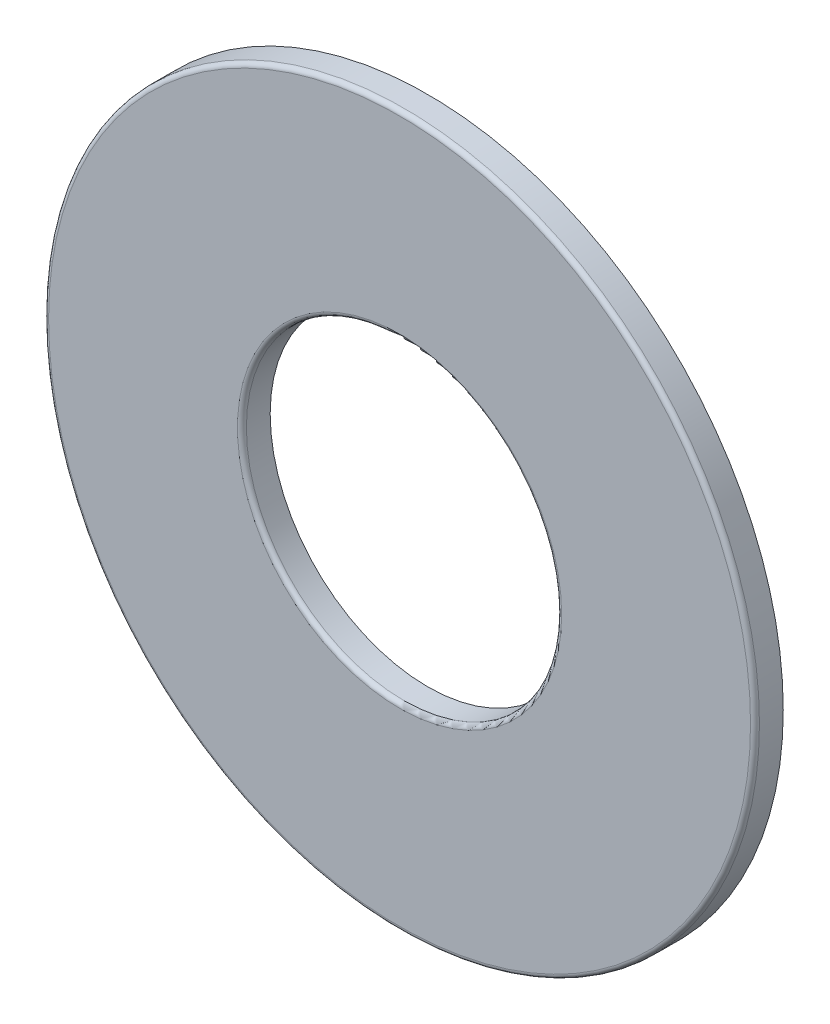
SolidWorks part; units mm, degrees
material "AISI 304"
ref_plane "Front Plane" through (0, 0, 0) normal (0, 0, 1) x (1, 0, 0)
ref_plane "Top Plane" through (0, 0, 0) normal (0, 1, 0) x (1, 0, 0)
ref_plane "Right Plane" through (0, 0, 0) normal (1, 0, 0) x (0, 0, -1)
sketch "Sketch1" plane through (0, 0, 0) normal (0, 1, 0) x (1, 0, 0)
  line L0 (-47.5, 1.5) -> (-47.5, 0.8)
  line L1 (-47.2, 0.5) -> (-46.5, 0.5)
  line L2 (-22.5, 0.5) -> (-21.8, 0.5)
  line L3 (-47.5, 4) -> (-47.5, 1.5)
  line L4 (-21.5, 0.8) -> (-21.5, 1.5)
  line L5 (-21.5, 4) -> (-21.5, 1.5)
  line L6 (-47.5, 4) -> (-47.8, 4)
  line L7 (-47.8, 4) -> (-47.8, 0.8)
  line L8 (0, 0) -> (0, 13.7827) construction
  line L9 (-46.5, 0.5) -> (-22.5, 0.5)
  line L10 (-47.2, 0.2) -> (-21.8, 0.2)
  line L11 (-21.2, 0.8) -> (-21.2, 4)
  line L12 (-21.2, 4) -> (-21.5, 4)
  arc A0 (-47.5, 0.8) -> (-47.2, 0.5) centre (-47.2, 0.8) ccw
  arc A1 (-47.2, 0.2) -> (-47.8, 0.8) centre (-47.2, 0.8) cw
  arc A2 (-21.8, 0.5) -> (-21.5, 0.8) centre (-21.8, 0.8) ccw
  arc A3 (-21.2, 0.8) -> (-21.8, 0.2) centre (-21.8, 0.8) cw
  dimension "D1" = 0.3
  dimension "D2" = 0.6
  dimension "D3" = 0.3
  dimension "D4" = 0.6
revolve "Revolve1" add sketch "Sketch1" angle 360 about L8
